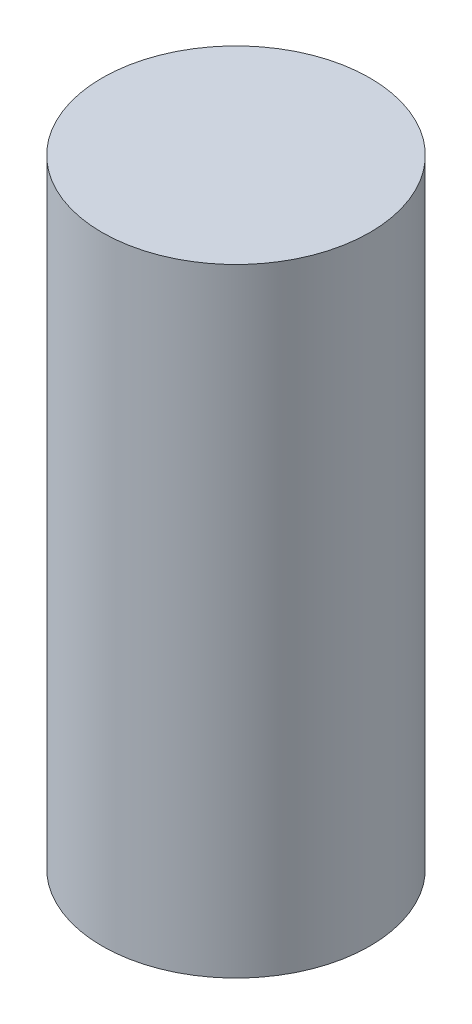
SolidWorks part; units mm, degrees
ref_plane "Front Plane" through (0, 0, 0) normal (0, 0, 1) x (1, 0, 0)
ref_plane "Top Plane" through (0, 0, 0) normal (0, 1, 0) x (1, 0, 0)
ref_plane "Right Plane" through (0, 0, 0) normal (1, 0, 0) x (0, 0, -1)
sketch "Sketch1" plane through (0, 0, 0) normal (0, 1, 0) x (1, 0, 0)
  circle A0 centre (0, 0) radius 32.5
  dimension "D1" = 65
extrude "Boss-Extrude1" add sketch "Sketch1" along normal blind 150
